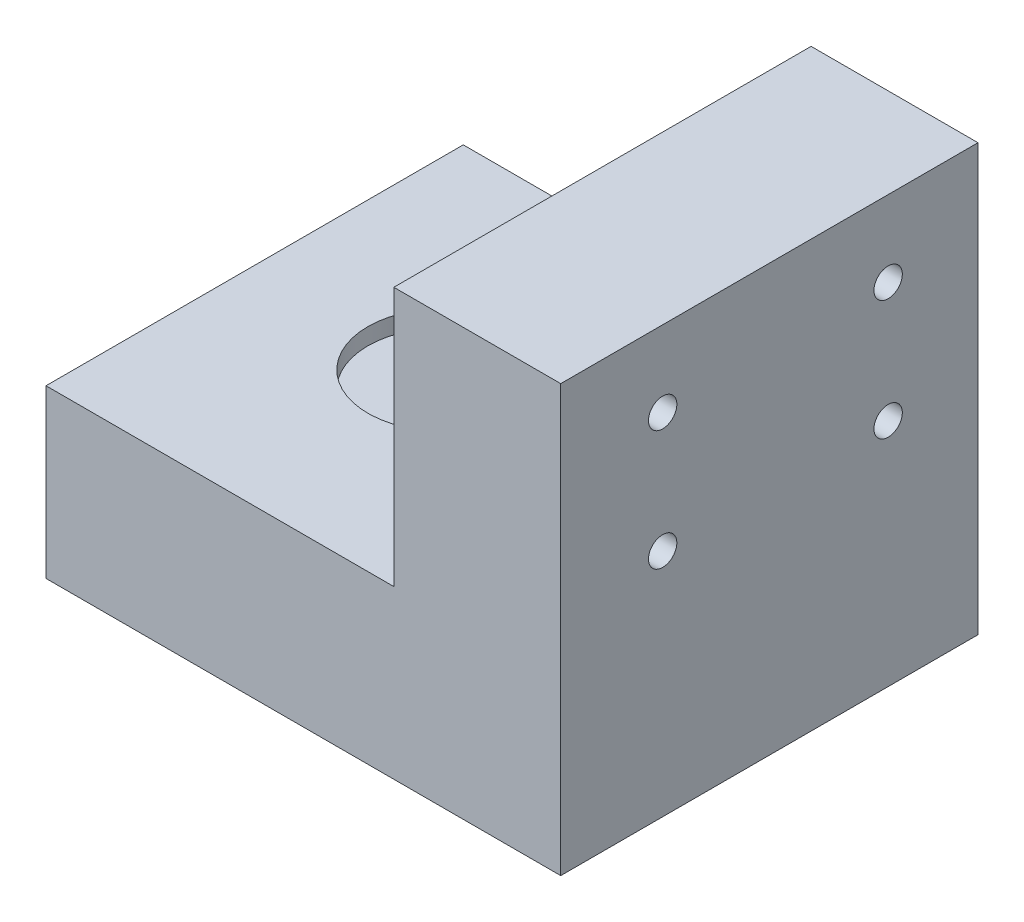
SolidWorks part; units mm, degrees
material "PLA"
ref_plane "Front Plane" through (0, 0, 0) normal (0, 0, 1) x (1, 0, 0)
ref_plane "Top Plane" through (0, 0, 0) normal (0, 1, 0) x (1, 0, 0)
ref_plane "Right Plane" through (0, 0, 0) normal (1, 0, 0) x (0, 0, -1)
sketch "Sketch1" plane through (0, 0, 0) normal (0, 0, 1) x (1, 0, 0)
  line L0 (-41.1765, 14.7365) -> (-41.1765, -36.3235)
  line L1 (-41.1765, -36.3235) -> (-102.8559, -36.3235)
  line L2 (-102.8559, -36.3235) -> (-102.8559, -16.3235)
  line L3 (-102.8559, -16.3235) -> (-61.1765, -16.3235)
  line L4 (-61.1765, -16.3235) -> (-61.1765, 14.7365)
  line L5 (-61.1765, 14.7365) -> (-41.1765, 14.7365)
  dimension "length 2 " = 51.06
  dimension "D1" = 61.6794
  dimension "D2" = 20
  dimension "D3" = 20
extrude "Boss-Extrude1" add sketch "Sketch1" along normal blind 50 contours L3 L4 L5 L0 L1 L2
sketch "Sketch2" plane through (-61.1765, 0, 0) normal (-1, 0, 0) x (0, 0, 1)
  circle A0 centre (10.7682, 5.6355) radius 1.7
  circle A1 centre (37.787, 5.6355) radius 1.7
  circle A2 centre (10.7682, -8.7408) radius 1.7
  circle A5 centre (37.787, -8.7408) radius 1.7
  dimension "D1" = 3.4
  dimension "D2" = 3.4
  dimension "D3" = 3.4
  dimension "D4" = 3.4
extrude "Cut-Extrude2" cut sketch "Sketch2" against normal through all contours A2 | A5 | A1 | A0
sketch "Sketch3" plane through (0, -16.3235, 0) normal (0, 1, 0) x (1, 0, 0)
  circle A0 centre (-80.7124, -24.5731) radius 3
  dimension "D1" = 6
extrude "Cut-Extrude3" cut sketch "Sketch3" against normal through all contours A0
sketch "Sketch4" plane through (0, -16.3235, 0) normal (0, 1, 0) x (1, 0, 0)
  circle A1 centre (-80.7124, -24.5731) radius 9
  dimension "D1" = 18
extrude "Cut-Extrude4" cut sketch "Sketch4" against normal blind 2 contours A1
equation "\"Elastic Modulus\"= 2346.5"
equation "\"yield strength\"= 49.5"
equation "\"moment area of inertia\"= ( \"base\" * \"width\" ^ 3 ) / 12"
equation "\"base\"= 50"
equation "\"applied moment\"= 18000"
equation "\"width\"= 20"
equation "\"max deflection\" = 0.30"
equation "\"length 2 \"= ( ( 2 * \"Elastic Modulus\" * \"moment area of inertia\" * \"max deflection\" ) / \"applied moment\" ) ^ ( 1 / 2 )"
equation "\"length 1\" = ( ( 3 * \"Elastic Modulus\" * \"max deflection\" * \"moment area of inertia\" ) / \"applied load\" ) ^ ( 1 / 3 )"
equation "\"applied load\"= 300"
equation "\"D1@Sketch1\"=\"length 1\""
equation "\"D2@Sketch1\"=\"width\""
equation "\"D3@Sketch1\"=\"width\""
